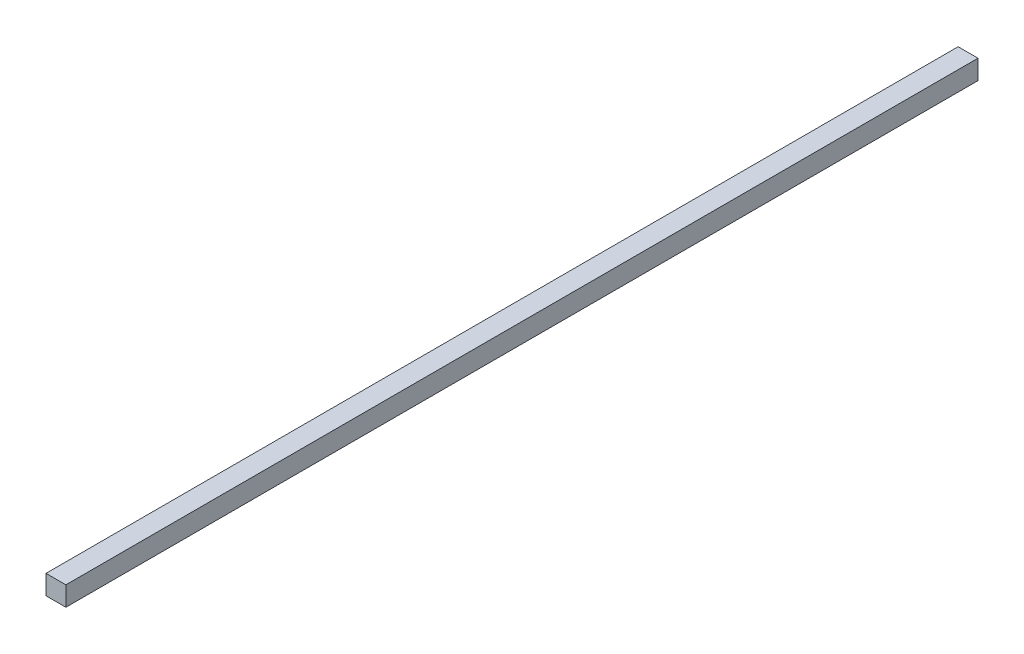
SolidWorks part; units mm, degrees
ref_plane "正面" through (0, 0, 0) normal (0, 0, 1) x (1, 0, 0)
ref_plane "平面" through (0, 0, 0) normal (0, 1, 0) x (1, 0, 0)
ref_plane "右側面" through (0, 0, 0) normal (1, 0, 0) x (0, 0, -1)
sketch "ｽｹｯﾁ1" plane through (0, 0, 0) normal (0, 0, 1) x (1, 0, 0)
  line L1 (-52.0353, 28.8521) -> (3.3136, 28.8521)
  line L2 (-52.0353, 28.8521) -> (-52.0353, -25.3192)
  line L3 (-52.0353, -25.3192) -> (3.3136, -25.3192)
  line L4 (3.3136, 28.8521) -> (3.3136, -25.3192)
  line L5 (-52.0353, 28.8521) -> (3.3136, -25.3192) construction
  line L6 (-52.0353, -25.3192) -> (3.3136, 28.8521) construction
  point P0 (-24.3608, 1.7665)
extrude "ﾎﾞｽ - 押し出し1" add sketch "ｽｹｯﾁ1" along normal blind 2540
